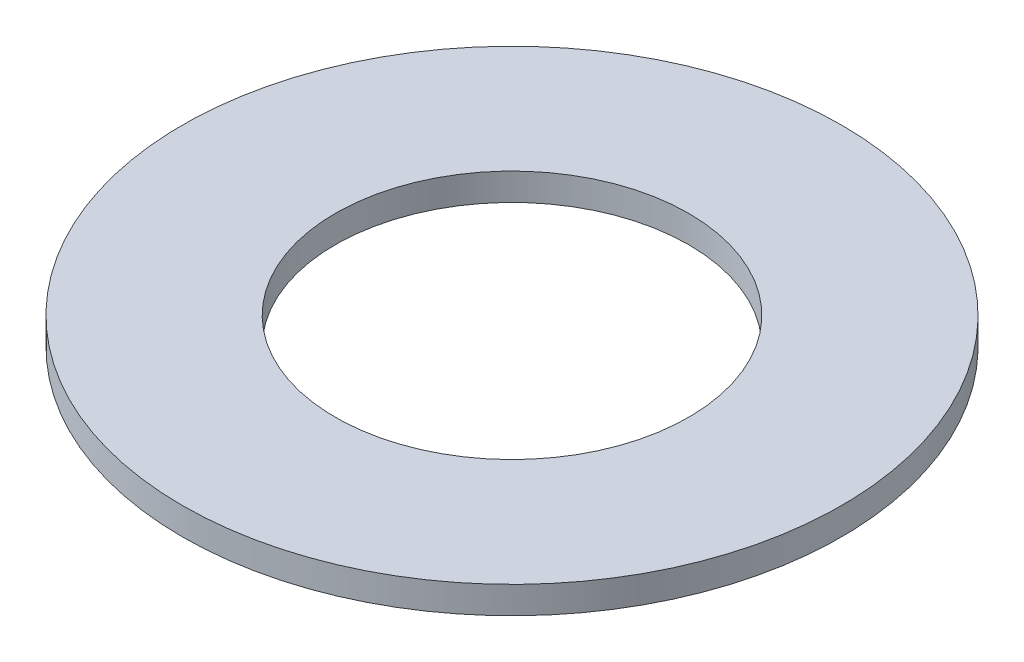
SolidWorks part; units mm, degrees
material "Accenditore"
ref_plane "Piano frontale" through (0, 0, 0) normal (0, 0, 1) x (1, 0, 0)
ref_plane "Piano superiore" through (0, 0, 0) normal (0, 1, 0) x (1, 0, 0)
ref_plane "Piano destro" through (0, 0, 0) normal (1, 0, 0) x (0, 0, -1)
sketch "Schizzo1" plane through (0, 0, 0) normal (0, 0, 1) x (1, 0, 0)
  line L0 (-26, 4) -> (-48.5, 4)
  line L1 (-48.5, 4) -> (-48.5, 0)
  line L2 (-48.5, 0) -> (-26, 0)
  line L3 (-26, 0) -> (-26, 4)
  line L4 (0, 0) -> (0, 36.3355) construction
  dimension "D1" = 52
  dimension "D2" = 4
  dimension "D3" = 97
revolve "Rivoluzione1" add sketch "Schizzo1" angle 360 about L4
